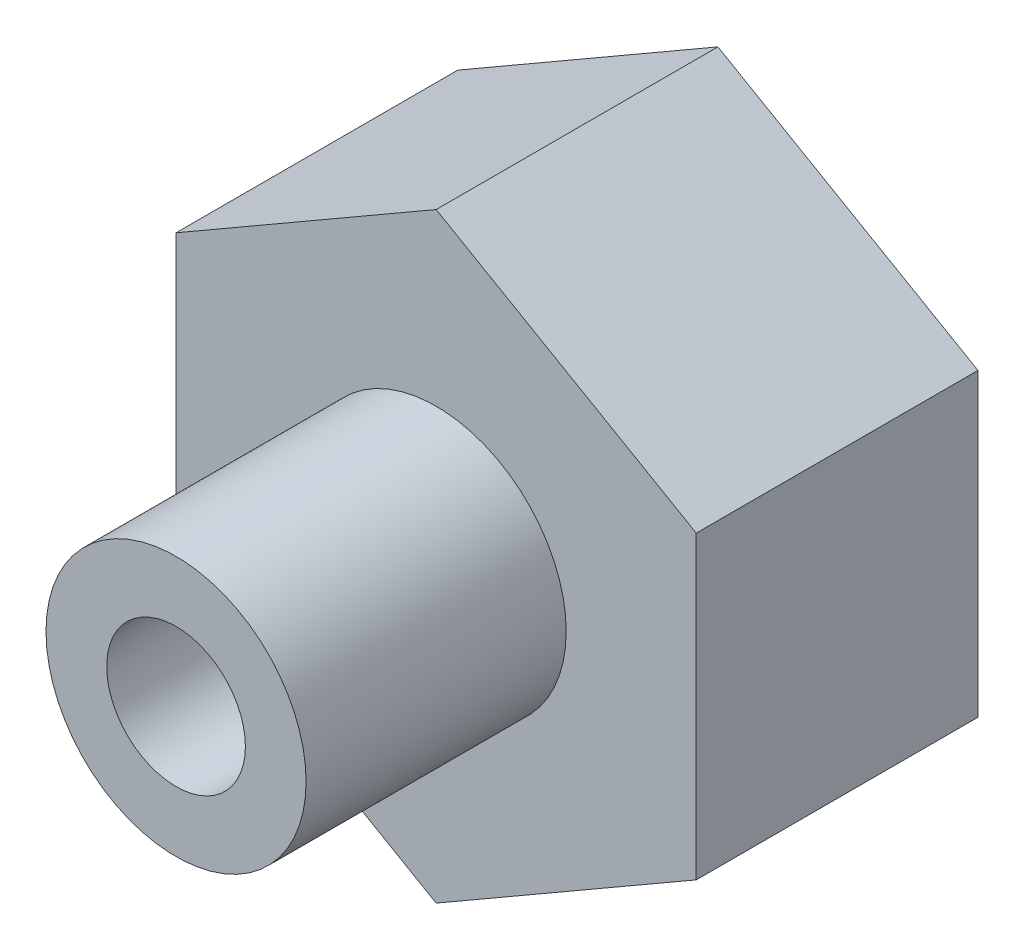
SolidWorks part; units mm, degrees
ref_plane "Front Plane" through (0, 0, 0) normal (0, 0, 1) x (1, 0, 0)
ref_plane "Top Plane" through (0, 0, 0) normal (0, 1, 0) x (1, 0, 0)
ref_plane "Right Plane" through (0, 0, 0) normal (1, 0, 0) x (0, 0, -1)
other "Configuration Table"
sketch "Sketch1" plane through (0, 0, 0) normal (0, 0, 1) x (1, 0, 0)
  line L0 (12, 6.9282) -> (0, 13.8564)
  line L1 (0, 13.8564) -> (-12, 6.9282)
  line L2 (-12, 6.9282) -> (-12, -6.9282)
  line L3 (-12, -6.9282) -> (0, -13.8564)
  line L4 (0, -13.8564) -> (12, -6.9282)
  line L5 (12, -6.9282) -> (12, 6.9282)
extrude "Hex_Nut" add sketch "Sketch1" along normal blind 13
sketch "Sketch2" plane through (0, 0, 0) normal (0, 0, 1) x (1, 0, 0)
  circle A0 centre (0, 0) radius 10.4775
  dimension "D1" = 20.955
extrude "Thread_Bore" cut sketch "Sketch2" along normal blind 11
sketch "Sketch3" plane through (0, 0, 0) normal (0, 0, 1) x (1, 0, 0)
  circle A0 centre (0, 0) radius 6
  dimension "D1" = 12
extrude "Push_Fit_Port" add sketch "Sketch3" along normal blind 12 from offset 13
sketch "Sketch4" plane through (0, 0, 0) normal (0, 0, 1) x (1, 0, 0)
  circle A0 centre (0, 0) radius 3.2
  dimension "D1" = 6.4
extrude "Push_Fit_Socket" cut sketch "Sketch4" against normal blind 10 from offset 25
equation "\"Jar_OD\"= 90  'ASSUMED - Part G fallback - jar outer diameter"
equation "\"Jar_H\"= 120  'ASSUMED - Part G fallback - jar height"
equation "\"Pump_L\"= 45  'ASSUMED - Part G fallback"
equation "\"Pump_W\"= 24  'ASSUMED - Part G fallback"
equation "\"Pump_H\"= 33  'ASSUMED - Part G fallback"
equation "\"Pump_Outlet_OD\"= 7.5  'ASSUMED - Part G fallback"
equation "\"Tube_OD\"= 8  'ASSUMED - Part G fallback"
equation "\"Tube_ID\"= 6  'ASSUMED - Part G fallback"
equation "\"TDS_Body_Dia\"= 12  'ASSUMED - Part G fallback"
equation "\"TDS_Wet_Len\"= 45  'ASSUMED - Part G fallback - length in water"
equation "\"DS_Tube_Dia\"= 6  'ASSUMED - Part G fallback"
equation "\"DS_Tube_Len\"= 50  'ASSUMED - Part G fallback"
equation "\"ORP_Body_Dia\"= 12  'ASSUMED - Part G fallback"
equation "\"ORP_Body_Len\"= 150  'ASSUMED - Part G fallback"
equation "\"ORP_Cap_Dia\"= 16  'ASSUMED - Part G fallback"
equation "\"Turb_W\"= 33  'ASSUMED - Part G fallback - head width"
equation "\"Turb_D\"= 28  'ASSUMED - Part G fallback - head depth"
equation "\"Turb_H\"= 30  'ASSUMED - Part G fallback - head height"
equation "\"Turb_Slot_W\"= 10  'ASSUMED - Part G fallback - slot width"
equation "\"Flow_L\"= 62  'ASSUMED - Part G fallback YF-S201"
equation "\"Flow_W\"= 36  'ASSUMED - Part G fallback"
equation "\"Flow_H\"= 35  'ASSUMED - Part G fallback"
equation "\"Thread_G12_OD\"= 20.955  'ASSUMED - Part G fallback thread G1/2 (major diameter)"
equation "\"Valve_L\"= 75  'ASSUMED - Part G fallback"
equation "\"Valve_W\"= 45  'ASSUMED - Part G fallback"
equation "\"Valve_H\"= 60  'ASSUMED - Part G fallback"
equation "\"Tee_L\"= 40  'ASSUMED - Part G fallback - overall length"
equation "\"Tee_Branch_L\"= 25  'ASSUMED - Part G fallback"
equation "\"Tee_OD\"= 12  'ASSUMED - Part G fallback"
equation "\"LED_Board_L\"= 20  'ASSUMED - Part G fallback"
equation "\"LED_Board_W\"= 20  'ASSUMED - Part G fallback - LED at centre"
equation "\"GUVA_L\"= 20  'ASSUMED - Part G fallback"
equation "\"GUVA_W\"= 12  'ASSUMED - Part G fallback - sensor at centre"
equation "\"Reed_L\"= 27  'ASSUMED - Part G fallback MC-38 half"
equation "\"Reed_W\"= 14  'ASSUMED - Part G fallback"
equation "\"Reed_H\"= 8  'ASSUMED - Part G fallback"
equation "\"ESP_L\"= 51  'ASSUMED - Part G fallback"
equation "\"ESP_W\"= 28  'ASSUMED - Part G fallback"
equation "\"TFT_L\"= 58  'ASSUMED - Part G fallback - board"
equation "\"TFT_W\"= 35  'ASSUMED - Part G fallback - board"
equation "\"TFT_Win_L\"= 35  'ASSUMED - Part G fallback - visible window"
equation "\"TFT_Win_W\"= 28  'ASSUMED - Part G fallback - visible window"
equation "\"Relay_L\"= 50  'ASSUMED - Part G fallback"
equation "\"Relay_W\"= 26  'ASSUMED - Part G fallback"
equation "\"Relay_H\"= 19  'ASSUMED - Part G fallback"
equation "\"Mosfet_L\"= 34  'ASSUMED - Part G fallback"
equation "\"Mosfet_W\"= 17  'ASSUMED - Part G fallback"
equation "\"Mosfet_H\"= 12  'ASSUMED - Part G fallback"
equation "\"TDS_Board_L\"= 42  'ASSUMED - Part G fallback"
equation "\"TDS_Board_W\"= 32  'ASSUMED - Part G fallback"
equation "\"Turb_Board_L\"= 38  'ASSUMED - Part G fallback"
equation "\"Turb_Board_W\"= 28  'ASSUMED - Part G fallback"
equation "\"BNC_Thread_Dia\"= 9.5  'ASSUMED - Part G fallback"
equation "\"Plate_L\"= 420  'ASSUMED - Part G fallback"
equation "\"Plate_W\"= 297  'ASSUMED - Part G fallback"
equation "\"Plate_T\"= 6  'ASSUMED - Part G fallback"
equation "\"Booster_L\"= 150  'ASSUMED - Part G fallback - booster pump"
equation "\"Booster_W\"= 95  'ASSUMED - Part G fallback"
equation "\"Booster_H\"= 100  'ASSUMED - Part G fallback"
equation "\"PTube_OD\"= 6.35  'ASSUMED - Part G fallback - product tube 1/4 inch"
equation "\"Qz_Out\"= 12  'ASSUMED - Part G fallback - quartz channel outside square"
equation "\"Qz_Path\"= 10  'ASSUMED - Part G fallback - quartz channel inside light path"
equation "\"Qz_L\"= 40  'ASSUMED - Part G fallback - quartz channel length"
equation "\"LED860_Dia\"= 5  'ASSUMED - Part G fallback - 860 nm LED"
equation "\"BPW_L\"= 5.4  'ASSUMED - Part G fallback - BPW34"
equation "\"BPW_W\"= 4.3  'ASSUMED - Part G fallback - BPW34"
equation "\"Cart_Dia\"= 50  'ASSUMED - Part G fallback - sediment and pre-carbon cartridges"
equation "\"Cart_L\"= 255  'ASSUMED - Part G fallback"
equation "\"UF_Dia\"= 50  'ASSUMED - Part G fallback - UF cartridge"
equation "\"UF_L\"= 260  'ASSUMED - Part G fallback"
equation "\"RO_Dia\"= 62  'ASSUMED - Part G fallback - RO membrane housing"
equation "\"RO_L\"= 300  'ASSUMED - Part G fallback"
equation "\"UVC_Dia\"= 40  'ASSUMED - Part G fallback - UV-C chamber"
equation "\"UVC_L\"= 300  'ASSUMED - Part G fallback"
equation "\"Tank_W\"= 260  'ASSUMED - Part G fallback - storage tank"
equation "\"Tank_D\"= 160  'ASSUMED - Part G fallback"
equation "\"Tank_H\"= 300  'ASSUMED - Part G fallback"
equation "\"Cab_W\"= 400  'ASSUMED - Part G fallback - purifier cabinet"
equation "\"Cab_D\"= 270  'ASSUMED - Part G fallback"
equation "\"Cab_H\"= 560  'ASSUMED - Part G fallback"
equation "\"ORP_Board_L\"= 40  'ASSUMED - Part G fallback - ORP buffer board"
equation "\"ORP_Board_W\"= 30  'ASSUMED - Part G fallback"
equation "\"Opt_Board_L\"= 50  'ASSUMED - Part G fallback - optical front-end board"
equation "\"Opt_Board_W\"= 40  'ASSUMED - Part G fallback"
equation "\"Buck_L\"= 43  'ASSUMED - Part G fallback - 12 V to 5 V buck module"
equation "\"Buck_W\"= 21  'ASSUMED - Part G fallback"
equation "\"Buck_H\"= 14  'ASSUMED - Part G fallback"
equation "\"BB_L\"= 165  'ASSUMED - Part G fallback - breadboard (As_Built_R3 only)"
equation "\"BB_W\"= 55  'ASSUMED - Part G fallback"
equation "\"BB_H\"= 10  'ASSUMED - Part G fallback"
equation "\"Cuv_W\"= 12.5  'ASSUMED - old R3 cuvette (station suppressed in SS4)"
equation "\"Cuv_D\"= 12.5  'ASSUMED - old R3 cuvette (station suppressed in SS4)"
equation "\"Cuv_H\"= 45  'ASSUMED - old R3 cuvette (station suppressed in SS4)"
equation "\"Probe_Clr\"= 0.3  'DESIGN VALUE - Part C rule 3 - printed probe hole = diameter + 0.3"
equation "\"Label_H\"= 0.6  'DESIGN VALUE - Part D - raised label height"
equation "\"D1@Sketch2\" = \"Thread_G12_OD\""
